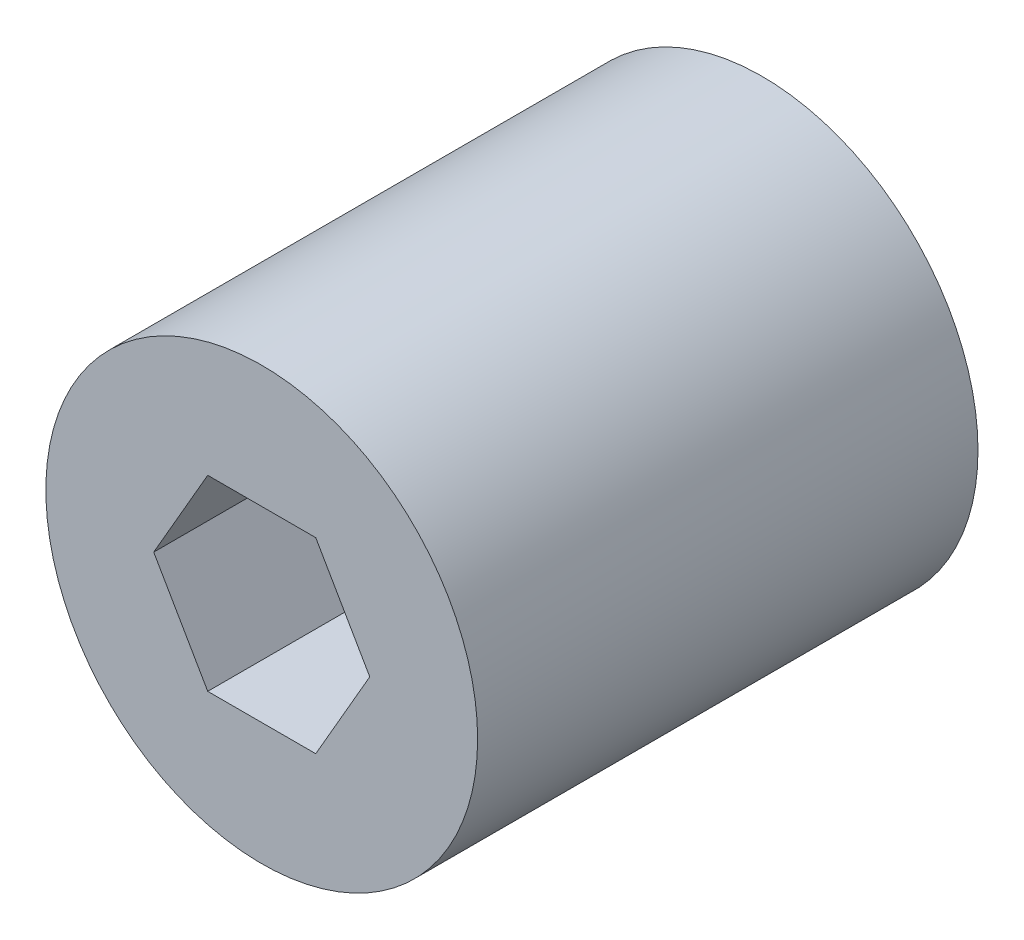
SolidWorks part; units mm, degrees
ref_plane "Front" through (0, 0, 0) normal (0, 0, 1) x (1, 0, 0)
ref_plane "Top" through (0, 0, 0) normal (0, 1, 0) x (1, 0, 0)
ref_plane "Right" through (0, 0, 0) normal (1, 0, 0) x (0, 0, -1)
sketch "Sketch1" plane through (0, 0, 0) normal (0, 0, 1) x (1, 0, 0)
  line L1 (3.0022, 0) -> (1.5011, 2.6)
  line L2 (1.5011, 2.6) -> (-1.5011, 2.6)
  line L3 (-1.5011, 2.6) -> (-3.0022, 0)
  line L4 (-3.0022, 0) -> (-1.5011, -2.6)
  line L5 (-1.5011, -2.6) -> (1.5011, -2.6)
  line L6 (1.5011, -2.6) -> (3.0022, 0)
  circle A0 centre (0, 0) radius 2.6 construction
  circle A1 centre (0, 0) radius 6
extrude "Boss-Extrude1" add sketch "Sketch1" along normal blind 13.9057
